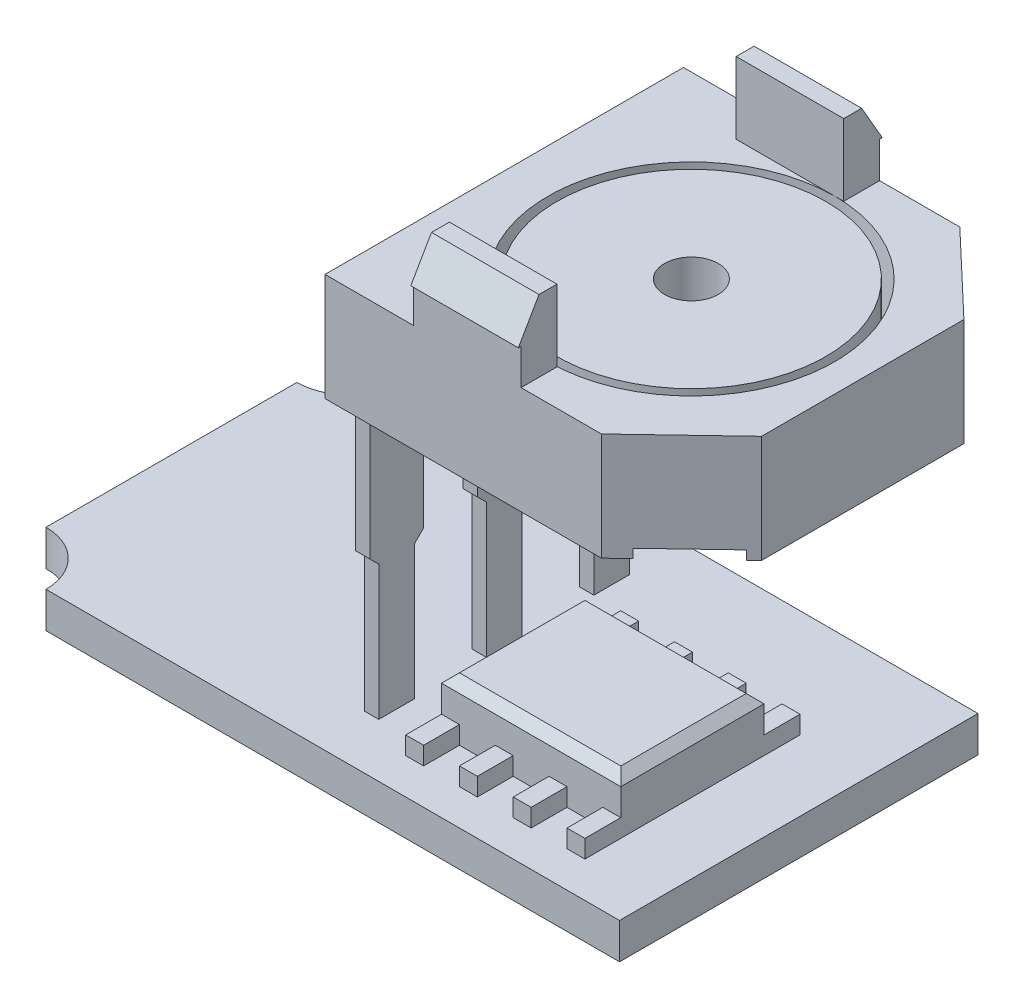
SolidWorks part; units mm, degrees
ref_plane "Front Plane" through (0, 0, 0) normal (0, 0, 1) x (1, 0, 0)
ref_plane "Top Plane" through (0, 0, 0) normal (0, 1, 0) x (1, 0, 0)
ref_plane "Right Plane" through (0, 0, 0) normal (1, 0, 0) x (0, 0, -1)
sketch "Sketch1" plane through (0, 0, 0) normal (0, 1, 0) x (1, 0, 0)
  line L1 (8.75, -5) -> (-7.25, -5)
  line L2 (8.75, -5) -> (8.75, 5)
  line L3 (8.75, 5) -> (-7.25, 5)
  line L4 (-8.75, -3.5) -> (-8.75, 3.5)
  line L5 (8.75, -5) -> (-8.75, 5) construction
  line L6 (8.75, 5) -> (-8.75, -5) construction
  arc A0 (-8.75, 3.5) -> (-7.25, 5) centre (-8.75, 5) ccw
  arc A1 (-7.25, -5) -> (-8.75, -3.5) centre (-8.75, -5) ccw
  point P0 (0, 0)
  dimension "D3" = 3
  dimension "D4" = 3
  dimension "D1" = 17.5
  dimension "D2" = 10
extrude "Boss-Extrude1" add sketch "Sketch1" along normal blind 1
sketch "Sketch2" plane through (0, 1, 0) normal (0, 1, 0) x (1, 0, 0)
  line L0 (-7.25, -5) -> (8.75, -5) construction
  line L1 (1.7839, 1) -> (6.7839, 1)
  line L2 (1.7839, 1) -> (1.7839, -3)
  line L3 (1.7839, -3) -> (6.7839, -3)
  line L4 (6.7839, 1) -> (6.7839, -3)
  line L5 (1.7839, 1) -> (6.7839, -3) construction
  line L6 (1.7839, -3) -> (6.7839, 1) construction
  point P0 (4.2839, -1)
  dimension "D1" = 4
  dimension "D2" = 4
  dimension "D3" = 5
extrude "Boss-Extrude2" add sketch "Sketch2" along normal blind 1.5
chamfer "Chamfer1" distance 0.25 angle 45 4 edges at (4.2839, 2.5, 3) (1.7839, 2.5, 1) (4.2839, 2.5, -1) (6.7839, 2.5, 1)
sketch "Sketch4" plane through (0, 1, 0) normal (0, 1, 0) x (1, 0, 0)
  line L0 (5.2839, -3) -> (5.2839, -4)
  line L1 (6.7839, -3) -> (6.2839, -3)
  line L2 (6.7839, -3) -> (6.7839, -4)
  line L3 (6.7839, -4) -> (6.2839, -4)
  line L4 (6.2839, -3) -> (6.2839, -4)
  line L5 (5.2839, -3) -> (4.7839, -3)
  line L6 (4.7839, -3) -> (4.7839, -4)
  line L7 (5.2839, -4) -> (4.7839, -4)
  line L8 (3.7839, -3) -> (3.7839, -4)
  line L9 (3.7839, -3) -> (3.2839, -3)
  line L10 (3.2839, -3) -> (3.2839, -4)
  line L11 (3.7839, -4) -> (3.2839, -4)
  line L12 (2.2839, -3) -> (2.2839, -4)
  line L13 (2.2839, -3) -> (1.7839, -3)
  line L14 (1.7839, -3) -> (1.7839, -4)
  line L15 (2.2839, -4) -> (1.7839, -4)
  line L16 (0.1839, -1) -> (9.8364, -1) construction
  line L17 (6.7839, 1) -> (1.7839, 1) construction
  line L18 (6.7839, 2) -> (6.2839, 2)
  line L19 (6.2839, 1) -> (6.2839, 2)
  line L20 (6.7839, 1) -> (6.2839, 1)
  line L21 (6.7839, 1) -> (6.7839, 2)
  line L22 (5.2839, 1) -> (4.7839, 1)
  line L23 (4.7839, 1) -> (4.7839, 2)
  line L24 (5.2839, 2) -> (4.7839, 2)
  line L25 (5.2839, 1) -> (5.2839, 2)
  line L26 (3.7839, 1) -> (3.2839, 1)
  line L27 (3.2839, 1) -> (3.2839, 2)
  line L28 (3.7839, 2) -> (3.2839, 2)
  line L29 (3.7839, 1) -> (3.7839, 2)
  line L30 (2.2839, 1) -> (1.7839, 1)
  line L31 (1.7839, 1) -> (1.7839, 2)
  line L32 (2.2839, 2) -> (1.7839, 2)
  line L33 (2.2839, 1) -> (2.2839, 2)
  dimension "D1" = 0.5
  dimension "D2" = 1
  dimension "D4" = 2
  dimension "D3" = 4
extrude "Boss-Extrude3" add sketch "Sketch4" along normal blind 0.5
ref_plane "Plane1" through (0.5339, 0, 0) normal (-1, 0, 0) x (0, 0, 1)
sketch "Sketch5" plane through (0.5339, 0, 0) normal (-1, 0, 0) x (0, 0, 1)
  line L1 (3.5, -0.6228) -> (2.5, -0.6228)
  line L2 (3.5, -0.6228) -> (3.5, 4.75)
  line L4 (2.5, -0.6228) -> (2.5, 4.75)
  line L5 (3, 3.3772) -> (3, -0.5728) construction
  line L6 (3.5, 3.3772) -> (2.5, 3.3772) construction
  line L7 (3.75, 5) -> (3.75, 11)
  line L8 (3.75, 11) -> (2.25, 11)
  line L9 (2.25, 5) -> (2.25, 11)
  line L10 (3, 3.3772) -> (3, 10.5692) construction
  line L11 (5, 1) -> (5, 0) construction
  line L12 (3.75, 5) -> (3.5, 4.75)
  line L13 (2.25, 5) -> (2.5, 4.75)
  line L14 (0.5, -0.6228) -> (-0.5, -0.6228)
  line L15 (-0.5, -0.6228) -> (-0.5, 4.75)
  line L16 (-0.75, 5) -> (-0.5, 4.75)
  line L17 (-0.75, 5) -> (-0.75, 11)
  line L18 (0.75, 11) -> (-0.75, 11)
  line L19 (0.75, 5) -> (0.75, 11)
  line L20 (0.75, 5) -> (0.5, 4.75)
  line L21 (0.5, -0.6228) -> (0.5, 4.75)
  line L22 (-2.5, -0.6228) -> (-3.5, -0.6228)
  line L23 (-3.5, -0.6228) -> (-3.5, 4.75)
  line L24 (-3.75, 5) -> (-3.5, 4.75)
  line L25 (-3.75, 5) -> (-3.75, 11)
  line L26 (-2.25, 11) -> (-3.75, 11)
  line L27 (-2.25, 5) -> (-2.25, 11)
  line L28 (-2.25, 5) -> (-2.5, 4.75)
  line L29 (-2.5, -0.6228) -> (-2.5, 4.75)
  dimension "D1" = 1
  dimension "D2" = 1.5
  dimension "D3" = 4
  dimension "D4" = 6
  dimension "D5" = 0.75
  dimension "D6" = 2
  dimension "D7" = 3
extrude "Boss-Extrude4" add sketch "Sketch5" along normal blind 0.4
ref_plane "Plane2" through (0, 0.5, 0) normal (0, 1, 0) x (1, 0, 0)
mirror "Mirror1" about plane through (0, 0.5, 0) normal (0, 1, 0) of "Boss-Extrude2", "Chamfer1", "Boss-Extrude3"
sketch "Sketch6" plane through (0, 11, 0) normal (0, 1, 0) x (1, 0, 0)
  line L0 (8.75, 5) -> (-7.25, 5) construction
  line L1 (0.5339, 5) -> (8.5339, 5)
  line L2 (0.5339, 5) -> (0.5339, -5)
  line L3 (0.5339, -5) -> (8.5339, -5)
  line L4 (10.5339, 3) -> (10.5339, -3)
  line L5 (0.5339, 2.25) -> (0.5339, 3.75) construction
  circle A0 centre (5.7539, 0) radius 4
  arc A1 (8.5339, -5) -> (10.5339, -3) centre (8.5339, -3) ccw
  arc A2 (10.5339, 3) -> (8.5339, 5) centre (8.5339, 3) ccw
  point P12 (10.5339, 5)
  point P15 (0.5339, 3)
  point P16 (0.5339, 0)
  dimension "D3" = 8
  dimension "D4" = 2
  dimension "D1" = 10
  dimension "D5" = 5.22
extrude "Boss-Extrude5" add sketch "Sketch6" along normal mid plane 3
sketch "Sketch7" plane through (0, 12.5, 0) normal (0, 1, 0) x (1, 0, 0)
  line L0 (3.0039, 5) -> (3.0039, 4)
  line L1 (8.5339, 5) -> (0.5339, 5) construction
  line L2 (3.0039, 4) -> (6.0039, 4)
  line L3 (6.0039, 4) -> (6.0039, 5)
  line L4 (6.0039, 5) -> (3.0039, 5)
  line L5 (5.7539, 7.0437) -> (5.7539, -7.0437) construction
  line L6 (2.7026, 0) -> (13.315, 0) construction
  line L7 (4.5039, 7.2742) -> (4.5039, -4.7277) construction
  circle A0 centre (5.7539, 0) radius 4 construction
  point P8 (5.7539, 0)
  dimension "D1" = 1
  dimension "D2" = 3
  dimension "D3" = 1.5
  dimension "D4" = 1.25
extrude "Boss-Extrude6" add sketch "Sketch7" along normal blind 2
sketch "Sketch8" plane through (6.0039, 0, 0) normal (1, 0, 0) x (0, 0, -1)
  line L0 (4.5, 14.5) -> (5.0774, 13.5)
  line L1 (4, 14.5) -> (5, 14.5) construction
  line L2 (5.0774, 13.5) -> (4.5, 13.5)
  line L3 (4.5, 13.5) -> (4.5, 14.5)
  point P4 (4.7887, 13.5)
  dimension "D1" = 60
  dimension "D2" = 1
extrude "Boss-Extrude7" add sketch "Sketch8" against normal up to surface (3 mm away) up to face at (3.0039, 13.5, -4.5)
sketch "Sketch9" plane through (6.0039, 0, 0) normal (1, 0, 0) x (0, 0, -1)
  line L0 (4.5, 14.5) -> (5.0774, 13.5) construction
  line L1 (4.5, 14.5) -> (5, 13.634)
  line L2 (4.5, 14.5) -> (5, 14.5)
  line L3 (5, 14.5) -> (5, 13.634)
extrude "Cut-Extrude1" cut sketch "Sketch9" against normal up to surface (3 mm away) up to face at (3.0039, 13.5191, -4.7253)
mirror "Mirror2" about plane through (0, 0, 0) normal (0, 0, 1) of "Boss-Extrude6", "Boss-Extrude7", "Cut-Extrude1"
sketch "Sketch10" plane through (0, 9.5, 0) normal (0, -1, 0) x (1, 0, 0)
  line L0 (8.5339, -5) -> (0.5339, -5) construction
  line L1 (10.5339, 3) -> (10.5339, -3) construction
  line L2 (0.5339, 5) -> (8.5339, 5) construction
  line L3 (6.5039, -5) -> (5.0039, -5)
  line L4 (10.5339, 0.75) -> (10.5339, -0.75)
  line L5 (5.0039, 5) -> (6.5039, 5)
  line L7 (6.9379, 0) -> (13.9283, 0) construction
  line L8 (5.7539, 6.4665) -> (5.7539, -6.9591) construction
  line L9 (9.1726, -0.75) -> (10.5339, -0.75)
  line L10 (9.1726, 0.75) -> (10.5339, 0.75)
  line L11 (6.5039, -3.4187) -> (6.5039, -5)
  line L12 (5.0039, -3.4187) -> (5.0039, -5)
  line L13 (2.3352, -0.75) -> (0.5339, -0.75)
  line L14 (2.3352, 0.75) -> (0.5339, 0.75)
  line L15 (5.0039, 3.4187) -> (5.0039, 5)
  line L16 (6.5039, 3.4187) -> (6.5039, 5)
  line L17 (0.5339, 0.75) -> (0.5339, -0.75)
  circle A6 centre (5.7539, 0) radius 2.5
  arc A7 (9.1726, 0.75) -> (6.5039, 3.4187) centre (5.7539, 0) ccw
  circle A8 centre (5.7539, 0) radius 4 construction
  arc A9 (9.1726, 0.75) -> (6.5039, 3.4187) centre (5.7539, 0) ccw
  arc A10 (9.1726, 0.75) -> (6.5039, 3.4187) centre (5.7539, 0) ccw
  arc A11 (9.1726, 0.75) -> (6.5039, 3.4187) centre (5.7539, 0) ccw
  arc A12 (6.5039, -3.4187) -> (9.1726, -0.75) centre (5.7539, 0) ccw
  arc A13 (6.5039, -3.4187) -> (9.1726, -0.75) centre (5.7539, 0) ccw
  arc A14 (6.5039, -3.4187) -> (9.1726, -0.75) centre (5.7539, 0) ccw
  arc A15 (6.5039, -3.4187) -> (9.1726, -0.75) centre (5.7539, 0) ccw
  arc A16 (2.3352, -0.75) -> (5.0039, -3.4187) centre (5.7539, 0) ccw
  arc A17 (2.3352, -0.75) -> (5.0039, -3.4187) centre (5.7539, 0) ccw
  arc A18 (2.3352, -0.75) -> (5.0039, -3.4187) centre (5.7539, 0) ccw
  arc A19 (2.3352, -0.75) -> (5.0039, -3.4187) centre (5.7539, 0) ccw
  arc A20 (5.0039, 3.4187) -> (2.3352, 0.75) centre (5.7539, 0) ccw
  arc A21 (5.0039, 3.4187) -> (2.3352, 0.75) centre (5.7539, 0) ccw
  arc A22 (5.0039, 3.4187) -> (2.3352, 0.75) centre (5.7539, 0) ccw
  arc A23 (5.0039, 3.4187) -> (2.3352, 0.75) centre (5.7539, 0) ccw
  point P40 (5.7539, 0)
  circle M25 centre (5.7539, 0) radius 4
  dimension "D1" = 5
  dimension "D2" = 1
  dimension "D3" = 1.5
  dimension "D4" = 0.75
  dimension "D5" = 4
extrude "Boss-Extrude8" add sketch "Sketch10" against normal blind 0.25 contours L15 A20 L14 L13 A16 L12 L11 A12 L9 L10 A7 L16 A6 M25
sketch "Sketch11" plane through (0, 9.5, 0) normal (0, -1, 0) x (1, 0, 0)
  line L0 (9.683, 0.75) -> (10.3226, 0.75)
  line L1 (10.3226, 0.75) -> (10.3226, 3.0687)
  line L2 (8.8226, 4.5687) -> (6.5039, 4.5687)
  line L3 (6.5039, 3.9291) -> (6.5039, 4.5687)
  line L4 (10.3226, -3.0687) -> (10.3226, -0.75)
  line L5 (9.683, -0.75) -> (10.3226, -0.75)
  line L6 (6.5039, -4.5687) -> (8.8226, -4.5687)
  line L7 (6.5039, -3.9291) -> (6.5039, -4.5687)
  line L8 (2.6852, -4.5687) -> (5.0039, -4.5687)
  line L9 (5.0039, -3.9291) -> (5.0039, -4.5687)
  line L10 (1.1852, -0.75) -> (1.1852, -3.0687)
  line L11 (1.8248, -0.75) -> (1.1852, -0.75)
  line L12 (1.1852, 3.0687) -> (1.1852, 0.75)
  line L13 (1.8248, 0.75) -> (1.1852, 0.75)
  line L14 (5.0039, 4.5687) -> (2.6852, 4.5687)
  line L15 (5.0039, 3.9291) -> (5.0039, 4.5687)
  arc A1 (10.3226, 3.0687) -> (8.8226, 4.5687) centre (8.8226, 3.0687) ccw
  arc A2 (6.5039, 3.9291) -> (9.683, 0.75) centre (5.7539, 0) cw
  arc A3 (9.683, -0.75) -> (6.5039, -3.9291) centre (5.7539, 0) cw
  arc A4 (8.8226, -4.5687) -> (10.3226, -3.0687) centre (8.8226, -3.0687) ccw
  arc A5 (5.0039, -3.9291) -> (1.8248, -0.75) centre (5.7539, 0) cw
  arc A6 (1.1852, -3.0687) -> (2.6852, -4.5687) centre (2.6852, -3.0687) ccw
  arc A7 (1.8248, 0.75) -> (5.0039, 3.9291) centre (5.7539, 0) cw
  arc A8 (2.6852, 4.5687) -> (1.1852, 3.0687) centre (2.6852, 3.0687) ccw
  point P36 (5.7539, 0)
  dimension "D3" = 1.5
  dimension "D1" = 1.15
  dimension "D2" = 1.15
  dimension "D4" = 4
extrude "Cut-Extrude2" cut sketch "Sketch11" against normal blind 0.25
sketch "Sketch13" plane through (0, 9.75, 0) normal (0, 1, 0) x (1, 0, 0)
  circle A0 centre (5.7539, 0) radius 2.5 construction
  arc A1 (5.7539, -4) -> (5.7539, 4) centre (5.7539, 0) ccw construction
  arc A2 (5.7539, 4) -> (5.7539, -4) centre (5.7539, 0) ccw construction
  circle A3 centre (5.7539, 0) radius 2.5
  arc A4 (5.7539, -4) -> (5.7539, 4) centre (5.7539, 0) ccw
  arc A5 (5.7539, 4) -> (5.7539, -4) centre (5.7539, 0) ccw
extrude "Boss-Extrude11" add sketch "Sketch13" along normal blind 0.25
sketch "Sketch14" plane through (0, 10, 0) normal (0, 1, 0) x (1, 0, 0)
  circle A0 centre (5.7539, 0) radius 2.5
extrude "Boss-Extrude12" add sketch "Sketch14" against normal blind 0.25
sketch "Sketch15" plane through (0, 10, 0) normal (0, 1, 0) x (1, 0, 0)
  circle A0 centre (5.7539, 0) radius 3.75
  arc A1 (5.7539, -4) -> (5.7539, 4) centre (5.7539, 0) ccw construction
  dimension "D1" = 0.25
extrude "Boss-Extrude13" add sketch "Sketch15" along normal up to surface (2.5 mm away) contours A0 up to face at (2.5739, 12.5, 0)
sketch "Sketch17" plane through (0, 12.5, 0) normal (0, 1, 0) x (1, 0, 0)
  circle A0 centre (5.7539, 0) radius 0.75
  circle A1 centre (5.7539, 0) radius 3.75 construction
  dimension "D1" = 1.5
extrude "Cut-Extrude3" cut sketch "Sketch17" against normal up to surface (3 mm away) up to face at (8.7249, 9.5, -2.971)
sketch "Sketch19" plane through (0, 12.5, 0) normal (0, 1, 0) x (1, 0, 0)
  line L0 (8.2428, 5) -> (10.5339, 2.8231)
  line L1 (8.2428, -5) -> (10.5339, -2.8231)
  line L2 (9.9481, -4.4142) -> (5.7539, 0) construction
  line L3 (5.7539, 0) -> (9.9481, 4.4142) construction
  line L4 (8.5339, 5) -> (6.0039, 5) construction
  line L5 (10.5339, -3) -> (10.5339, 3) construction
  line L6 (10.5339, 2.8231) -> (10.5339, 3)
  line L7 (8.5339, 5) -> (8.2428, 5)
  line L8 (6.0039, -5) -> (8.5339, -5) construction
  line L9 (10.5339, -3) -> (10.5339, -2.8231)
  line L10 (8.2428, -5) -> (8.5339, -5)
  line L11 (10.5339, 2.8231) -> (10.5339, 3)
  arc A0 (10.5339, 3) -> (8.5339, 5) centre (8.5339, 3) ccw construction
  arc A1 (8.5339, -5) -> (10.5339, -3) centre (8.5339, -3) ccw construction
  circle A2 centre (5.7539, 0) radius 3.75 construction
  arc A3 (10.5339, 3) -> (8.5339, 5) centre (8.5339, 3) ccw
  arc A4 (8.5339, -5) -> (10.5339, -3) centre (8.5339, -3) ccw
  line M2 (6.0039, -5) -> (8.5339, -5)
  arc M3 (8.5339, -5) -> (10.5339, -3) centre (8.5339, -3) ccw
  line M4 (10.5339, -3) -> (10.5339, 3)
  arc M5 (10.5339, 3) -> (8.5339, 5) centre (8.5339, 3) ccw
  line M6 (8.5339, 5) -> (6.0039, 5)
  dimension "D1" = 0.75
  dimension "D2" = 0.75
extrude "Cut-Extrude5" cut sketch "Sketch19" against normal blind 7 contours L1 M2 M3 M4 | L0 M6 M4 M5
